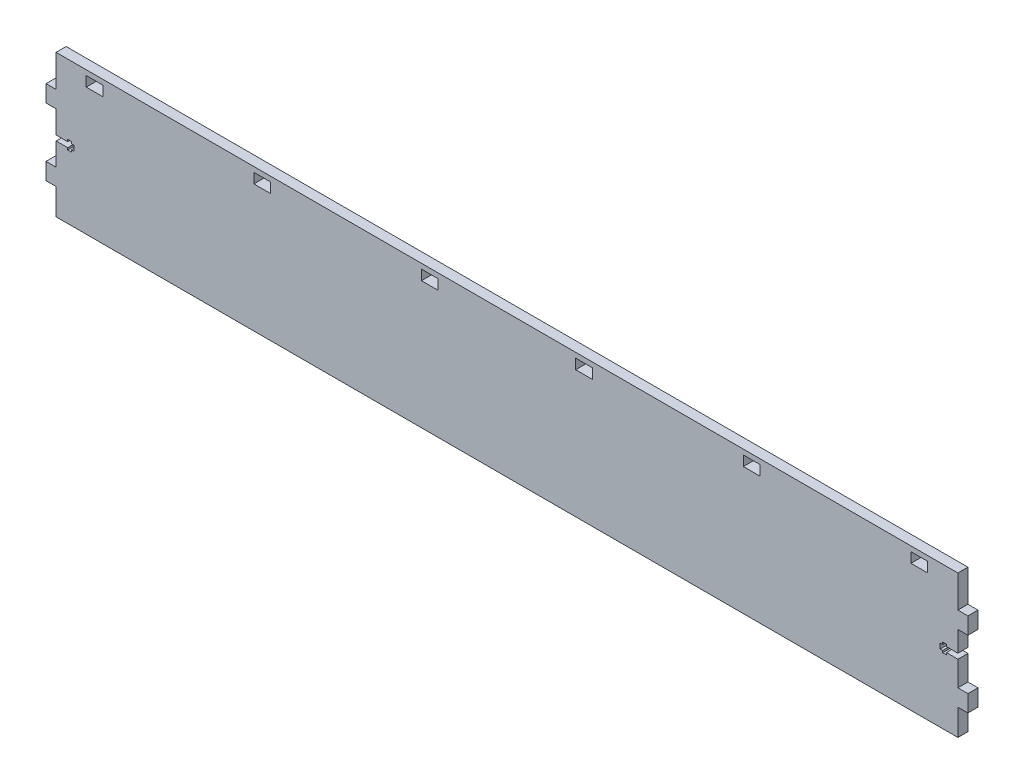
SolidWorks part; units mm, degrees
material "Клен"
ref_plane "Спереди" through (0, 0, 0) normal (0, 0, 1) x (1, 0, 0)
ref_plane "Сверху" through (0, 0, 0) normal (0, 1, 0) x (1, 0, 0)
ref_plane "Справа" through (0, 0, 0) normal (1, 0, 0) x (0, 0, -1)
sketch "Эскиз1" plane through (0, 0, 0) normal (0, 0, 1) x (1, 0, 0)
  line L0 (-216.686, -77) -> (394.4072, -77) construction
  line L1 (-164.3736, 3) -> (373.6264, 3)
  line L2 (-164.3736, 3) -> (-164.3736, -16.1682)
  line L3 (-164.3736, -82) -> (373.6264, -82)
  line L5 (-248.7285, -41.25) -> (424.967, -41.25) construction
  line L6 (373.6264, 3) -> (373.6264, -16.1682)
  line L8 (-164.3736, -16.1682) -> (-170.3736, -16.1682)
  line L10 (-164.3736, -26.1682) -> (-170.3736, -26.1682)
  line L11 (-170.3736, -16.1682) -> (-170.3736, -26.1682)
  line L12 (-170.3736, -66.3318) -> (-170.3736, -56.3318)
  line L13 (-164.3736, -56.3318) -> (-170.3736, -56.3318)
  line L14 (-164.3736, -66.3318) -> (-170.3736, -66.3318)
  line L15 (-164.3736, -66.3318) -> (-164.3736, -82)
  line L24 (104.6264, 35.0605) -> (104.6264, -109.5252) construction
  line L25 (373.6264, -66.3318) -> (379.6264, -66.3318)
  line L26 (373.6264, -56.3318) -> (379.6264, -56.3318)
  line L27 (379.6264, -66.3318) -> (379.6264, -56.3318)
  line L28 (379.6264, -16.1682) -> (379.6264, -26.1682)
  line L29 (373.6264, -26.1682) -> (379.6264, -26.1682)
  line L30 (373.6264, -16.1682) -> (379.6264, -16.1682)
  line L31 (373.6264, -26.1682) -> (373.6264, -38.45)
  line L32 (373.6264, -66.3318) -> (373.6264, -82)
  line L33 (-202.0067, 0) -> (411.5465, 0) construction
  line L35 (-146.3736, 0) -> (-136.3736, 0)
  line L36 (-146.3736, 0) -> (-146.3736, -6)
  line L37 (-146.3736, -6) -> (-136.3736, -6)
  line L38 (-136.3736, 0) -> (-136.3736, -6)
  line L48 (-164.3736, -26.1682) -> (-164.3022, -39.7)
  line L58 (-157.4307, -39.7) -> (-157.4307, -38.5)
  line L59 (-164.3022, -42.8) -> (-164.3736, -56.3318)
  line L60 (-164.2307, -39.7) -> (-157.4307, -39.7)
  line L61 (-155.2307, -39.7) -> (-153.7307, -39.7)
  line L62 (-157.4307, -38.5) -> (-155.2307, -38.5)
  line L63 (-164.2307, -38.5) -> (-164.2307, -44) construction
  line L64 (-155.2307, -44) -> (-157.4307, -44)
  line L65 (-153.7307, -39.7) -> (-153.7307, -42.8)
  line L66 (-155.2307, -38.5) -> (-155.2307, -39.7)
  line L67 (-157.4307, -44) -> (-157.4307, -42.8)
  line L68 (-157.4307, -42.8) -> (-164.2307, -42.8)
  line L69 (-155.2307, -42.8) -> (-155.2307, -44)
  line L70 (-153.7307, -42.8) -> (-155.2307, -42.8)
  line L71 (-174.5096, -40) -> (-172.1812, -40) construction
  line L72 (-164.3022, -39.7) -> (-164.2307, -39.7)
  line L73 (-164.3022, -42.8) -> (-164.2307, -42.8)
  line L74 (366.7549, -38.45) -> (373.6264, -38.45)
  line L75 (366.7549, -42.75) -> (366.7549, -41.55)
  line L76 (366.7549, -41.55) -> (373.6264, -41.55)
  line L77 (373.6264, -41.55) -> (373.6264, -56.3318)
  line L78 (363.0549, -41.55) -> (363.0549, -38.45)
  line L79 (363.0549, -38.45) -> (364.5549, -38.45)
  line L80 (364.5549, -38.45) -> (364.5549, -37.25)
  line L81 (364.5549, -37.25) -> (366.7549, -37.25)
  line L82 (366.7549, -37.25) -> (366.7549, -38.45)
  line L95 (-46.3736, 0) -> (-46.3736, -6)
  line L96 (-46.3736, 0) -> (-36.3736, 0)
  line L97 (-36.3736, 0) -> (-36.3736, -6)
  line L98 (-46.3736, -6) -> (-36.3736, -6)
  line L99 (53.6264, 0) -> (53.6264, -6)
  line L100 (53.6264, 0) -> (63.6264, 0)
  line L101 (63.6264, 0) -> (63.6264, -6)
  line L102 (53.6264, -6) -> (63.6264, -6)
  line L103 (155.6264, 0) -> (145.6264, 0)
  line L104 (145.6264, 0) -> (145.6264, -6)
  line L105 (155.6264, -6) -> (145.6264, -6)
  line L106 (155.6264, 0) -> (155.6264, -6)
  line L107 (255.6264, 0) -> (245.6264, 0)
  line L108 (245.6264, 0) -> (245.6264, -6)
  line L109 (255.6264, -6) -> (245.6264, -6)
  line L110 (255.6264, 0) -> (255.6264, -6)
  line L111 (355.6264, -6) -> (345.6264, -6)
  line L112 (345.6264, 0) -> (345.6264, -6)
  line L113 (355.6264, 0) -> (345.6264, 0)
  line L116 (355.6264, 0) -> (355.6264, -6)
  line L130 (363.0549, -41.55) -> (364.5549, -41.55)
  line L131 (364.5549, -41.55) -> (364.5549, -42.75)
  line L133 (364.5549, -42.75) -> (366.7549, -42.75)
  dimension "D1" = 538
  dimension "D2" = 85
  dimension "D3" = 5
  dimension "D4" = 35.75
  dimension "D5" = 15.0818
  dimension "D6" = 10
  dimension "D7" = 6
  dimension "D8" = 3
  dimension "D9" = 6
  dimension "D10" = 10
  dimension "D11" = 18
  dimension "D12" = 3
extrude "Бобышка-Вытянуть1" add sketch "Эскиз1" along normal blind 6
